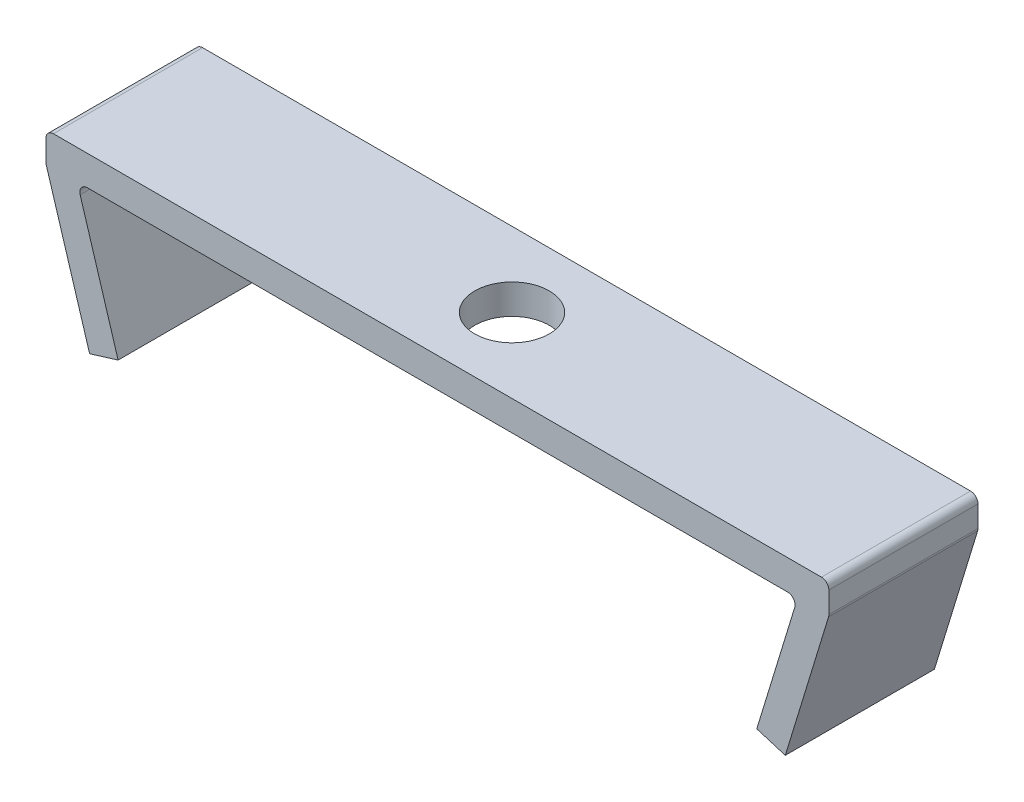
SolidWorks part; units mm, degrees
material "Chrome Stainless Steel"
ref_plane "Front Plane" through (0, 0, 0) normal (0, 0, 1) x (1, 0, 0)
ref_plane "Top Plane" through (0, 0, 0) normal (0, 1, 0) x (1, 0, 0)
ref_plane "Right Plane" through (0, 0, 0) normal (1, 0, 0) x (0, 0, -1)
sketch "Sketch2" plane through (0, 0, 0) normal (0, 0, 1) x (1, 0, 0)
  line L0 (66.675, -2.54) -> (59.2488, -26.8301)
  line L1 (-66.675, 2.54) -> (66.675, 2.54)
  line L2 (-66.675, 2.54) -> (-66.675, -2.54)
  line L3 (-61.3629, -2.54) -> (61.3629, -2.54)
  line L4 (66.675, 2.54) -> (66.675, -2.54)
  line L5 (-66.675, 2.54) -> (66.675, -2.54) construction
  line L6 (-66.675, -2.54) -> (66.675, 2.54) construction
  line L7 (59.2488, -26.8301) -> (54.3907, -25.3449)
  line L8 (54.3907, -25.3449) -> (61.3629, -2.54)
  line L9 (0, -13.97) -> (0, 13.97) construction
  line L10 (-54.3907, -25.3449) -> (-61.3629, -2.54)
  line L11 (-59.2488, -26.8301) -> (-54.3907, -25.3449)
  line L12 (-66.675, -2.54) -> (-59.2488, -26.8301)
  point P0 (0, 0)
  dimension "D1" = 133.35
  dimension "D2" = 5.08
  dimension "D3" = 73
  dimension "D4" = 25.4
  dimension "D5" = 5.08
extrude "Boss-Extrude1" add sketch "Sketch2" along normal mid plane 25.4
sketch "Sketch3" plane through (0, 2.54, 0) normal (0, 1, 0) x (1, 0, 0)
  circle A0 centre (0, 0) radius 6.35
  dimension "D1" = 12.7
extrude "Cut-Extrude1" cut sketch "Sketch3" against normal through all
fillet "Fillet1" radius 1.27 6 edges at (-61.3629, -2.54, 0) (-66.675, -2.54, 0) (-66.675, 2.54, 0) (66.675, -2.54, 0) (66.675, 2.54, 0) (61.3629, -2.54, 0)
